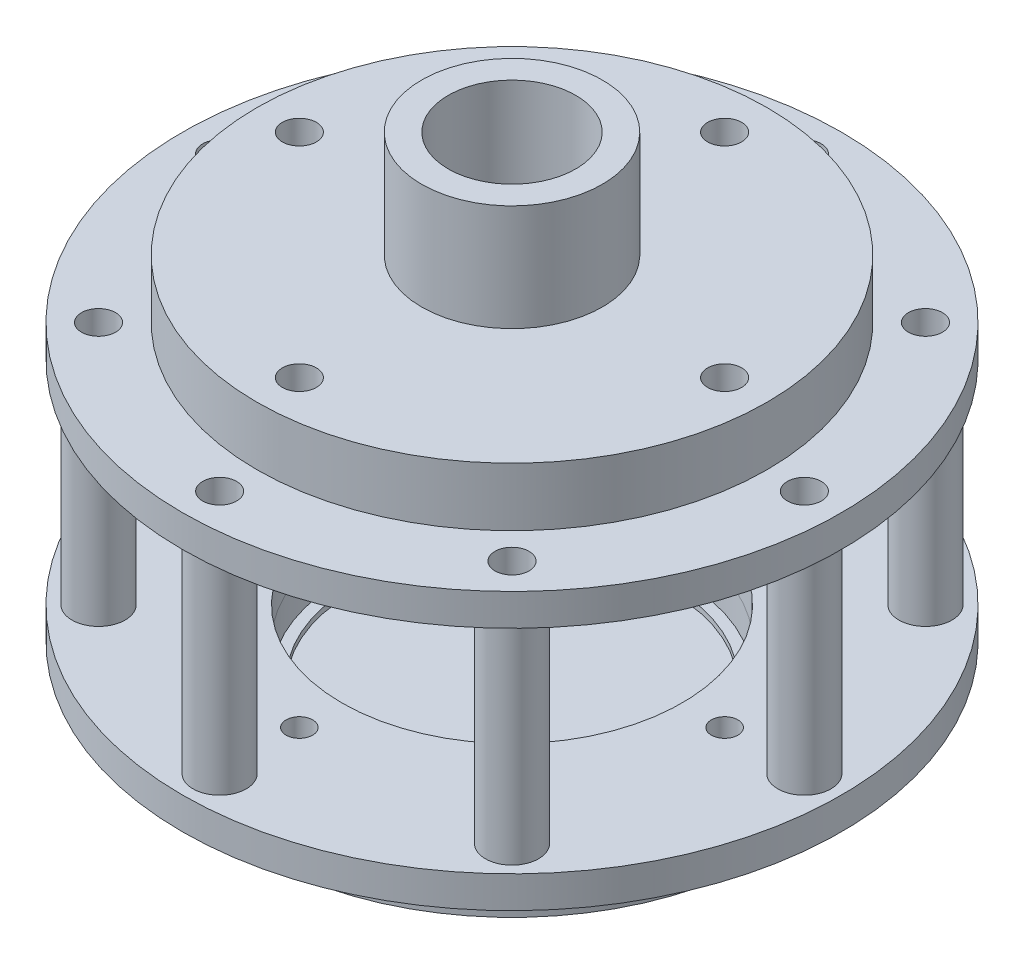
SolidWorks part; units mm, degrees
ref_plane "正面" through (0, 0, 0) normal (0, 0, 1) x (1, 0, 0)
ref_plane "平面" through (0, 0, 0) normal (0, 1, 0) x (1, 0, 0)
ref_plane "右側面" through (0, 0, 0) normal (1, 0, 0) x (0, 0, -1)
sketch "ｽｹｯﾁ1" plane through (0, 0, 0) normal (0, 1, 0) x (1, 0, 0)
  circle A0 centre (0, 0) radius 31
  circle A1 centre (0, 0) radius 27.5 construction
  circle A2 centre (0, 27.5) radius 1.6
  circle A3 centre (19.4454, 19.4454) radius 1.6
  circle A4 centre (27.5, 0) radius 1.6
  circle A5 centre (19.4454, -19.4454) radius 1.6
  circle A6 centre (0, -27.5) radius 1.6
  circle A7 centre (-19.4454, -19.4454) radius 1.6
  circle A8 centre (-27.5, 0) radius 1.6
  circle A9 centre (-19.4454, 19.4454) radius 1.6
  circle A10 centre (0, 0) radius 16
  circle A11 centre (0, 0) radius 20 construction
  circle A12 centre (20, 0) radius 1.25
  circle A13 centre (0, -20) radius 1.25
  circle A14 centre (-20, 0) radius 1.25
  circle A15 centre (0, 20) radius 1.25
  point P22 (0, 0)
  point P33 (0, 0)
  dimension "D1" = 55
  dimension "D2" = 62
  dimension "D3" = 3.2
  dimension "D5" = 32
  dimension "D6" = 40
  dimension "D7" = 2.5
  dimension "D4" = 8
  dimension "D8" = 4
extrude "ﾎﾞｽ - 押し出し1" add sketch "ｽｹｯﾁ1" along normal blind 3
sketch "ｽｹｯﾁ2" plane through (0, 3, 0) normal (0, 1, 0) x (1, 0, 0)
  circle A0 centre (0, 27.5) radius 2.5
  circle A1 centre (19.4454, 19.4454) radius 2.5
  circle A2 centre (27.5, 0) radius 2.5
  circle A3 centre (19.4454, -19.4454) radius 2.5
  circle A4 centre (0, -27.5) radius 2.5
  circle A5 centre (-19.4454, -19.4454) radius 2.5
  circle A6 centre (-27.5, 0) radius 2.5
  circle A7 centre (-19.4454, 19.4454) radius 2.5
  circle A8 centre (-19.4454, 19.4454) radius 1.6 construction
  point P19 (0, 0)
  dimension "D1" = 5
  dimension "D2" = 8
extrude "ｶｯﾄ - 押し出し1" cut sketch "ｽｹｯﾁ2" against normal blind 0.5
sketch "ｽｹｯﾁ3" plane through (0, 2.5, 0) normal (0, 1, 0) x (1, 0, 0)
  circle A1 centre (-27.5, 0) radius 2.5 construction
  circle A3 centre (-27.5, 0) radius 2.5
  circle A4 centre (-27.5, 0) radius 1.25
  circle A6 centre (-19.4454, 19.4454) radius 2.5
  circle A7 centre (-19.4454, 19.4454) radius 1.25
  circle A8 centre (0, 27.5) radius 2.5
  circle A9 centre (0, 27.5) radius 1.25
  circle A10 centre (19.4454, 19.4454) radius 2.5
  circle A11 centre (19.4454, 19.4454) radius 1.25
  circle A12 centre (27.5, 0) radius 2.5
  circle A13 centre (27.5, 0) radius 1.25
  circle A14 centre (19.4454, -19.4454) radius 2.5
  circle A15 centre (19.4454, -19.4454) radius 1.25
  circle A16 centre (0, -27.5) radius 2.5
  circle A17 centre (0, -27.5) radius 1.25
  circle A18 centre (-19.4454, -19.4454) radius 2.5
  circle A19 centre (-19.4454, -19.4454) radius 1.25
  circle A20 centre (-19.4454, 19.4454) radius 1.6 construction
  point P29 (0, 0)
  dimension "D1" = 2.5
  dimension "D2" = 8
extrude "ﾎﾞｽ - 押し出し2" add sketch "ｽｹｯﾁ3" along normal blind 21 separate body
sketch "ｽｹｯﾁ4" plane through (0, 0, 0) normal (0, -1, 0) x (1, 0, 0)
  circle A0 centre (0, 0) radius 24
  circle A1 centre (20, 0) radius 1.6
  circle A2 centre (0, -20) radius 1.6
  circle A3 centre (-20, 0) radius 1.6
  circle A4 centre (0, 20) radius 1.6
  circle A5 centre (0, 20) radius 1.25 construction
  circle A6 centre (0, 0) radius 16 construction
  circle A7 centre (0, 0) radius 16
  point P15 (0, 0)
  dimension "D1" = 48
  dimension "D2" = 3.2
  dimension "D3" = 4
extrude "ﾎﾞｽ - 押し出し3" add sketch "ｽｹｯﾁ4" along normal blind 3 separate body
sketch "ｽｹｯﾁ5" plane through (0, -3, 0) normal (0, -1, 0) x (1, 0, 0)
  circle A0 centre (0, 0) radius 24
  circle A1 centre (0, 0) radius 15
  circle A2 centre (0, 0) radius 24 construction
  circle A3 centre (0, 0) radius 16 construction
  circle A5 centre (20, 0) radius 1.6
  circle A6 centre (20, 0) radius 1.6 construction
  circle A7 centre (0, -20) radius 1.6
  circle A8 centre (-20, 0) radius 1.6
  circle A9 centre (0, 20) radius 1.6
  point P23 (0, 0)
  dimension "D1" = 1
  dimension "D2" = 4
extrude "ﾎﾞｽ - 押し出し4" add sketch "ｽｹｯﾁ5" along normal blind 0.5 separate body
sketch "ｽｹｯﾁ6" plane through (0, -3.5, 0) normal (0, -1, 0) x (1, 0, 0)
  circle A0 centre (0, 0) radius 24
  circle A1 centre (0, 20) radius 1.6 construction
  circle A2 centre (20, 0) radius 1.6 construction
  circle A3 centre (0, -20) radius 1.6 construction
  circle A4 centre (0, 20) radius 1.6
  circle A5 centre (20, 0) radius 1.6
  circle A6 centre (0, -20) radius 1.6
  circle A7 centre (-20, 0) radius 1.6 construction
  circle A8 centre (-20, 0) radius 1.6
  circle A9 centre (0, 0) radius 24 construction
extrude "ﾎﾞｽ - 押し出し5" add sketch "ｽｹｯﾁ6" along normal blind 2 separate body
sketch "ｽｹｯﾁ7" plane through (0, -5.5, 0) normal (0, -1, 0) x (1, 0, 0)
  circle A0 centre (0, 0) radius 8.5
  dimension "D1" = 17
extrude "ﾎﾞｽ - 押し出し6" add sketch "ｽｹｯﾁ7" along normal blind 10 separate body
ref_plane "平面1" through (0, 13, 0) normal (0, 1, 0) x (1, 0, 0)
mirror "ﾐﾗｰ1" about plane through (0, 13, 0) normal (0, 1, 0) of bodies 102
ref_plane "平面2" through (0, 13, 0) normal (0, 1, 0) x (1, 0, 0)
combine bodies "組み合わせ1" operation type add bodies to combine 114 113 112
mirror "ﾐﾗｰ2" about plane through (0, 13, 0) normal (0, 1, 0)
sketch "ｽｹｯﾁ8" plane through (0, 31.5, 0) normal (0, 1, 0) x (1, 0, 0)
  circle A0 centre (0, 0) radius 8.5
  dimension "D1" = 17
extrude "ﾎﾞｽ - 押し出し7" add sketch "ｽｹｯﾁ8" along normal blind 10
sketch "ｽｹｯﾁ9" plane through (0, 41.5, 0) normal (0, 1, 0) x (1, 0, 0)
  circle A0 centre (0, 0) radius 6
  dimension "D1" = 12
extrude "ｶｯﾄ - 押し出し2" cut sketch "ｽｹｯﾁ9" against normal up to surface (18.5 mm away) up to face at (0, 23, -25)
